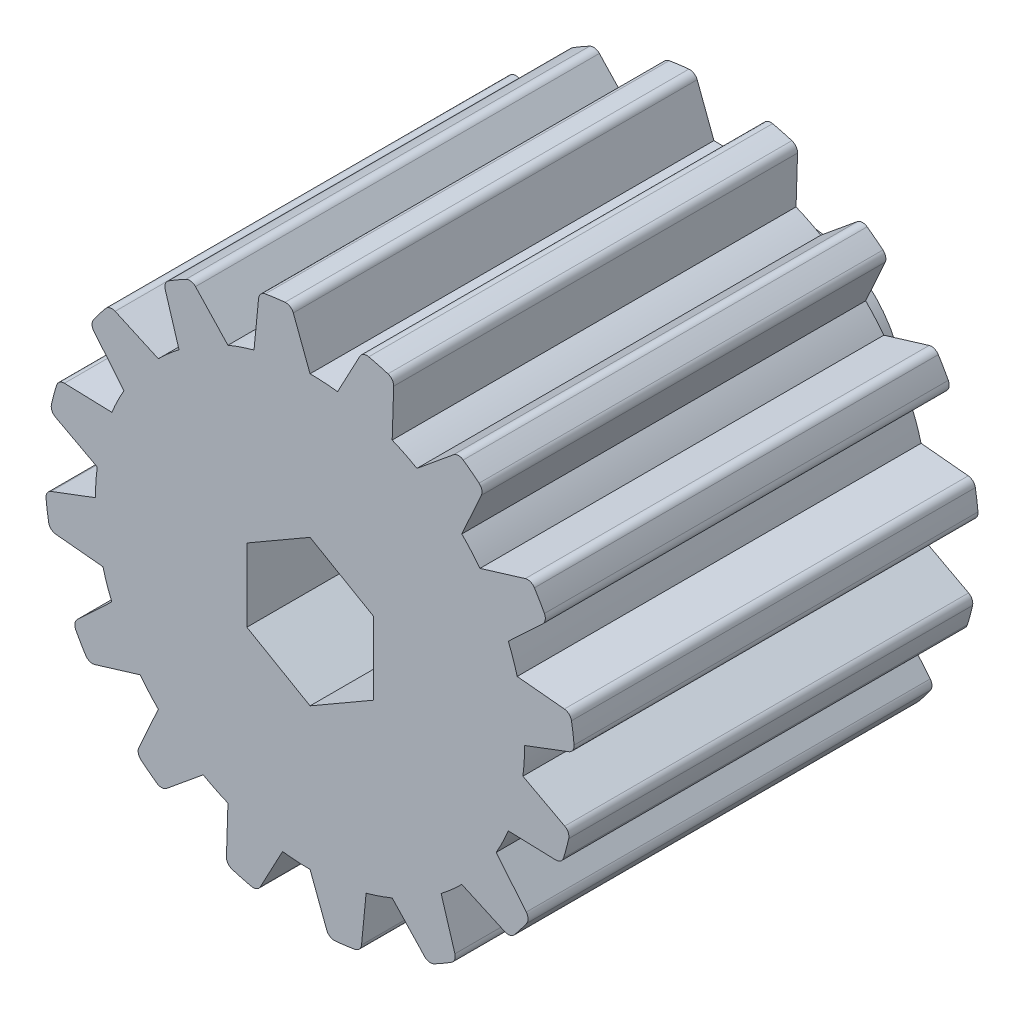
SolidWorks part; units mm, degrees
ref_plane "Alzado" through (0, 0, 0) normal (0, 0, 1) x (1, 0, 0)
ref_plane "Planta" through (0, 0, 0) normal (0, 1, 0) x (1, 0, 0)
ref_plane "Vista lateral" through (0, 0, 0) normal (1, 0, 0) x (0, 0, -1)
sketch "Croquis2" plane through (0, 0, 0) normal (0, 0, 1) x (1, 0, 0)
  line L0 (0, 0) -> (0, 7.9702) construction
  line L2 (-2.0817, 7.6936) -> (-1.9112, 9.4453)
  line L3 (-1.0408, 7.8319) -> (0, 0) construction
  line L4 (0, 7.9702) -> (-0.6221, 9.6166)
  line L5 (1.021, 7.9046) -> (1.8489, 9.4577)
  line L6 (3.0501, 7.3635) -> (3.1053, 9.1227)
  line L7 (3.9682, 6.9122) -> (5.3274, 8.0302)
  line L8 (5.6358, 5.6358) -> (6.3601, 7.2399)
  line L9 (6.3113, 4.8674) -> (7.9949, 5.3803)
  line L10 (7.3635, 3.0501) -> (8.6465, 4.2549)
  line L11 (7.6936, 2.0817) -> (9.4453, 1.9112)
  line L12 (7.9702, 0) -> (9.6166, 0.6221)
  line L13 (7.9046, -1.021) -> (9.4577, -1.8489)
  line L14 (7.3635, -3.0501) -> (9.1227, -3.1053)
  line L15 (6.9122, -3.9682) -> (8.0302, -5.3274)
  line L16 (5.6358, -5.6358) -> (7.2399, -6.3601)
  line L17 (4.8674, -6.3113) -> (5.3803, -7.9949)
  line L18 (3.0501, -7.3635) -> (4.2549, -8.6465)
  line L19 (2.0817, -7.6936) -> (1.9112, -9.4453)
  line L20 (0, -7.9702) -> (0.6221, -9.6166)
  line L21 (-1.021, -7.9046) -> (-1.8489, -9.4577)
  line L22 (-3.0501, -7.3635) -> (-3.1053, -9.1227)
  line L23 (-3.9682, -6.9122) -> (-5.3274, -8.0302)
  line L24 (-5.6358, -5.6358) -> (-6.3601, -7.2399)
  line L25 (-6.3113, -4.8674) -> (-7.9949, -5.3803)
  line L26 (-7.3635, -3.0501) -> (-8.6465, -4.2549)
  line L27 (-7.6936, -2.0817) -> (-9.4453, -1.9112)
  line L28 (-7.9702, 0) -> (-9.6166, -0.6221)
  line L29 (-7.9046, 1.021) -> (-9.4577, 1.8489)
  line L30 (-7.3635, 3.0501) -> (-9.1227, 3.1053)
  line L31 (-6.9122, 3.9682) -> (-8.0302, 5.3274)
  line L32 (-5.6358, 5.6358) -> (-7.2399, 6.3601)
  line L33 (-4.8674, 6.3113) -> (-5.3803, 7.9949)
  line L34 (-3.0501, 7.3635) -> (-4.2549, 8.6465)
  arc A0 (-4.8674, 6.3113) -> (-5.6358, 5.6358) centre (0, 0) ccw
  arc A1 (-7.5914, 6.2764) -> (-8.0413, 5.6886) centre (0, 0) ccw
  arc A2 (-1.6636, 9.7085) -> (-1.9112, 9.4453) centre (-1.6129, 9.4128) ccw
  arc A3 (-0.9298, 9.806) -> (-0.6221, 9.6166) centre (-0.9015, 9.5074) cw
  arc A4 (2.1783, 9.6061) -> (1.8489, 9.4577) centre (2.112, 9.3135) ccw
  arc A5 (2.8935, 9.4154) -> (3.1053, 9.1227) centre (2.8054, 9.1286) cw
  arc A6 (5.6886, 8.0413) -> (5.3274, 8.0302) centre (5.5153, 7.7964) ccw
  arc A7 (6.2764, 7.5914) -> (6.3601, 7.2399) centre (6.0852, 7.3602) cw
  arc A8 (8.3328, 5.2523) -> (7.9949, 5.3803) centre (8.0791, 5.0923) ccw
  arc A9 (8.7037, 4.6117) -> (8.6465, 4.2549) centre (8.4387, 4.4712) cw
  arc A10 (9.7085, 1.6636) -> (9.4453, 1.9112) centre (9.4128, 1.6129) ccw
  arc A11 (9.806, 0.9298) -> (9.6166, 0.6221) centre (9.5074, 0.9015) cw
  arc A12 (9.6061, -2.1783) -> (9.4577, -1.8489) centre (9.3135, -2.112) ccw
  arc A13 (9.4154, -2.8935) -> (9.1227, -3.1053) centre (9.1286, -2.8054) cw
  arc A14 (8.0413, -5.6886) -> (8.0302, -5.3274) centre (7.7964, -5.5153) ccw
  arc A15 (7.5914, -6.2764) -> (7.2399, -6.3601) centre (7.3602, -6.0852) cw
  arc A16 (5.2523, -8.3328) -> (5.3803, -7.9949) centre (5.0923, -8.0791) ccw
  arc A17 (4.6117, -8.7037) -> (4.2549, -8.6465) centre (4.4712, -8.4387) cw
  arc A18 (1.6636, -9.7085) -> (1.9112, -9.4453) centre (1.6129, -9.4128) ccw
  arc A19 (0.9298, -9.806) -> (0.6221, -9.6166) centre (0.9015, -9.5074) cw
  arc A20 (-2.1783, -9.6061) -> (-1.8489, -9.4577) centre (-2.112, -9.3135) ccw
  arc A21 (-2.8935, -9.4154) -> (-3.1053, -9.1227) centre (-2.8054, -9.1286) cw
  arc A22 (-5.6886, -8.0413) -> (-5.3274, -8.0302) centre (-5.5153, -7.7964) ccw
  arc A23 (-6.2764, -7.5914) -> (-6.3601, -7.2399) centre (-6.0852, -7.3602) cw
  arc A24 (-8.3328, -5.2523) -> (-7.9949, -5.3803) centre (-8.0791, -5.0923) ccw
  arc A25 (-8.7037, -4.6117) -> (-8.6465, -4.2549) centre (-8.4387, -4.4712) cw
  arc A26 (-9.7085, -1.6636) -> (-9.4453, -1.9112) centre (-9.4128, -1.6129) ccw
  arc A27 (-9.806, -0.9298) -> (-9.6166, -0.6221) centre (-9.5074, -0.9015) cw
  arc A28 (-9.6061, 2.1783) -> (-9.4577, 1.8489) centre (-9.3135, 2.112) ccw
  arc A29 (-9.4154, 2.8935) -> (-9.1227, 3.1053) centre (-9.1286, 2.8054) cw
  arc A30 (-8.0413, 5.6886) -> (-8.0302, 5.3274) centre (-7.7964, 5.5153) ccw
  arc A31 (-7.5914, 6.2764) -> (-7.2399, 6.3601) centre (-7.3602, 6.0852) cw
  arc A32 (-5.2523, 8.3328) -> (-5.3803, 7.9949) centre (-5.0923, 8.0791) ccw
  arc A33 (-4.6117, 8.7037) -> (-4.2549, 8.6465) centre (-4.4712, 8.4387) cw
  arc A34 (-4.6117, 8.7037) -> (-5.2523, 8.3328) centre (0, 0) ccw
  arc A35 (-0.9298, 9.806) -> (-1.6636, 9.7085) centre (0, 0) ccw
  arc A36 (2.8935, 9.4154) -> (2.1783, 9.6061) centre (0, 0) ccw
  arc A37 (6.2764, 7.5914) -> (5.6886, 8.0413) centre (0, 0) ccw
  arc A38 (8.7037, 4.6117) -> (8.3328, 5.2523) centre (0, 0) ccw
  arc A39 (9.4154, -2.8935) -> (9.6061, -2.1783) centre (0, 0) ccw
  arc A40 (7.5914, -6.2764) -> (8.0413, -5.6886) centre (0, 0) ccw
  arc A41 (-9.4154, 2.8935) -> (-9.6061, 2.1783) centre (0, 0) ccw
  arc A42 (-9.806, -0.9298) -> (-9.7085, -1.6636) centre (0, 0) ccw
  arc A43 (-8.7037, -4.6117) -> (-8.3328, -5.2523) centre (0, 0) ccw
  arc A44 (-6.2764, -7.5914) -> (-5.6886, -8.0413) centre (0, 0) ccw
  arc A45 (-2.8935, -9.4154) -> (-2.1783, -9.6061) centre (0, 0) ccw
  arc A46 (0.9298, -9.806) -> (1.6636, -9.7085) centre (0, 0) ccw
  arc A47 (4.6117, -8.7037) -> (5.2523, -8.3328) centre (0, 0) ccw
  arc A48 (-2.0817, 7.6936) -> (-3.0501, 7.3635) centre (0, 0) ccw
  arc A49 (1.021, 7.9046) -> (0, 7.9702) centre (0, 0) ccw
  arc A50 (3.9682, 6.9122) -> (3.0501, 7.3635) centre (0, 0) ccw
  arc A51 (6.3113, 4.8674) -> (5.6358, 5.6358) centre (0, 0) ccw
  arc A52 (7.6936, 2.0817) -> (7.3635, 3.0501) centre (0, 0) ccw
  arc A53 (7.9046, -1.021) -> (7.9702, 0) centre (0, 0) ccw
  arc A54 (9.806, 0.9298) -> (9.7085, 1.6636) centre (0, 0) ccw
  arc A55 (6.9122, -3.9682) -> (7.3635, -3.0501) centre (0, 0) ccw
  arc A56 (4.8674, -6.3113) -> (5.6358, -5.6358) centre (0, 0) ccw
  arc A57 (2.0817, -7.6936) -> (3.0501, -7.3635) centre (0, 0) ccw
  arc A58 (-1.021, -7.9046) -> (0, -7.9702) centre (0, 0) ccw
  arc A59 (-3.9682, -6.9122) -> (-3.0501, -7.3635) centre (0, 0) ccw
  arc A60 (-6.3113, -4.8674) -> (-5.6358, -5.6358) centre (0, 0) ccw
  arc A61 (-7.6936, -2.0817) -> (-7.3635, -3.0501) centre (0, 0) ccw
  arc A62 (-7.9046, 1.021) -> (-7.9702, 0) centre (0, 0) ccw
  arc A63 (-6.9122, 3.9682) -> (-7.3635, 3.0501) centre (0, 0) ccw
  dimension "D1" = 2.1
  dimension "D2" = 19.7
  dimension "D3" = 15.9404
  dimension "D6" = 0.6
  dimension "D4" = 1.76
extrude "Saliente-Extruir1" add sketch "Croquis2" along normal blind 15
sketch "Croquis5" plane through (0, 0, 0) normal (0, 0, -1) x (-1, 0, 0)
  circle A0 centre (0, 0) radius 4.5
  dimension "D1" = 9
extrude "Saliente-Extruir2" add sketch "Croquis5" along normal blind 6
scale "Escala1" scale about origin uniform scaling yes scale factor 1.5
sketch "Croquis7" plane through (0, 0, -9) normal (0, 0, -1) x (-1, 0, 0)
  circle A0 centre (0, 0) radius 10
  dimension "D1" = 20
extrude "Cortar-Extruir3" cut sketch "Croquis7" against normal blind 5.8 and the other way through all
sketch "Croquis8" plane through (0, 0, -3.2) normal (0, 0, -1) x (-1, 0, 0)
  circle A3 centre (0, 0) radius 5.5
  point P1 (-0.8117, -0.4992)
  point P2 (0, 0)
  dimension "D1" = 11
extrude "Saliente-Extruir3" add sketch "Croquis8" along normal blind 1.87
sketch "Croquis10" plane through (0, 0, 22.5) normal (0, 0, 1) x (1, 0, 0)
  line L0 (0, 3.95) -> (0, -5.201) construction
  line L1 (0, 3.95) -> (-3.4208, 1.975) construction
  line L2 (-3.4208, 1.975) -> (-3.4208, -1.975) construction
  line L3 (-3.4208, -1.975) -> (0, -3.95) construction
  line L4 (0, -3.95) -> (3.4208, -1.975) construction
  line L5 (3.4208, -1.975) -> (3.4208, 1.975) construction
  line L6 (3.4208, 1.975) -> (0, 3.95) construction
  line L8 (0, 4.0655) -> (-3.5208, 2.0327)
  line L9 (-3.5208, 2.0327) -> (-3.5208, -2.0327)
  line L10 (-3.5208, -2.0327) -> (0, -4.0655)
  line L11 (0, -4.0655) -> (3.5208, -2.0327)
  line L12 (3.5208, -2.0327) -> (3.5208, 2.0327)
  line L13 (3.5208, 2.0327) -> (0, 4.0655)
  circle A0 centre (0, 0) radius 3.95 construction
  circle A1 centre (0, 0) radius 3.95 construction
  circle A3 centre (0, 0) radius 3.5208 construction
  dimension "D1" = 7.9
  dimension "D2" = 0.1
extrude "Cortar-Extruir4" cut sketch "Croquis10" against normal through all both and the other way through all
